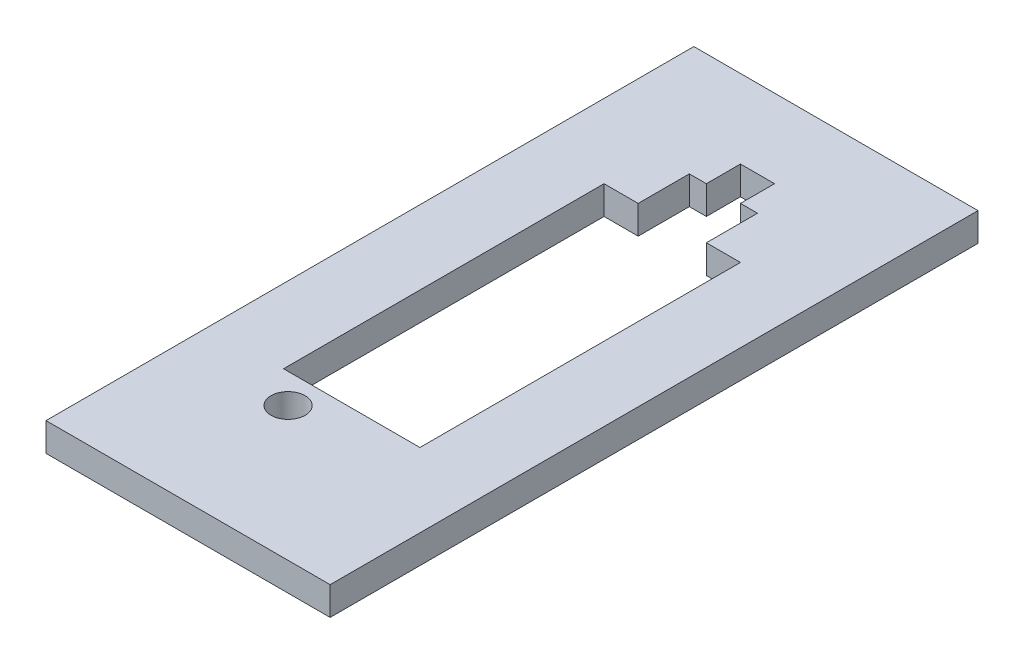
SolidWorks part; units mm, degrees
material "Spruce"
ref_plane "Front Plane" through (0, 0, 0) normal (0, 0, 1) x (1, 0, 0)
ref_plane "Top Plane" through (0, 0, 0) normal (0, 1, 0) x (1, 0, 0)
ref_plane "Right Plane" through (0, 0, 0) normal (1, 0, 0) x (0, 0, -1)
sketch "Sketch1" plane through (0, 0, 0) normal (0, 1, 0) x (1, 0, 0)
  line L1 (-15.875, 36.195) -> (15.875, 36.195)
  line L2 (-15.875, 36.195) -> (-15.875, -36.195)
  line L3 (-15.875, -36.195) -> (15.875, -36.195)
  line L4 (15.875, 36.195) -> (15.875, -36.195)
  line L5 (-15.875, 36.195) -> (15.875, -36.195) construction
  line L6 (-15.875, -36.195) -> (15.875, 36.195) construction
  point P0 (0, 0)
  dimension "D1" = 72.39
  dimension "D2" = 31.75
extrude "Boss-Extrude1" add sketch "Sketch1" along normal blind 3.175
sketch "Sketch3" plane through (0, 3.175, 0) normal (0, 1, 0) x (1, 0, 0)
  line L1 (-7.62, 17.907) -> (7.62, 17.907)
  line L2 (-7.62, 17.907) -> (-7.62, -17.907)
  line L3 (-7.62, -17.907) -> (7.62, -17.907)
  line L4 (7.62, 17.907) -> (7.62, -17.907)
  line L5 (-7.62, 17.907) -> (7.62, -17.907) construction
  line L6 (-7.62, -17.907) -> (7.62, 17.907) construction
  point P0 (0, 0)
  dimension "D1" = 15.24
  dimension "D2" = 35.814
extrude "Cut-Extrude1" cut sketch "Sketch3" against normal up to surface (3.175 mm away) up to face at (0, 0, 0)
sketch "Sketch4" plane through (0, 3.175, 0) normal (0, 1, 0) x (1, 0, 0)
  line L2 (0, 17.907) -> (0, 25.527) construction
  line L3 (0, 36.195) -> (0, 17.907) construction
  line L4 (15.875, 36.195) -> (-15.875, 36.195) construction
  line L6 (7.62, 17.907) -> (-7.62, 17.907) construction
  line L17 (-3.81, 17.907) -> (3.81, 17.907)
  line L18 (-3.81, 23.622) -> (3.81, 23.622)
  line L19 (-3.81, 23.622) -> (-3.81, 17.907)
  line L21 (3.81, 23.622) -> (3.81, 17.907)
  line L22 (-3.81, 23.622) -> (0, 17.907) construction
  line L23 (0, 17.907) -> (3.81, 23.622) construction
  line L25 (-1.905, 27.432) -> (1.905, 27.432)
  line L26 (-1.905, 27.432) -> (-1.905, 23.622)
  line L27 (-1.905, 23.622) -> (1.905, 23.622)
  line L28 (1.905, 27.432) -> (1.905, 23.622)
  line L29 (-1.905, 27.432) -> (1.905, 23.622) construction
  line L30 (-1.905, 23.622) -> (1.905, 27.432) construction
  circle A0 centre (-3.81, -21.209) radius 1.905
  point P5 (0, 17.907)
  point P7 (0, 17.907)
  point P15 (0, 17.907)
  line M7 (-7.62, 17.907) -> (7.62, 17.907)
  dimension "D1" = 7.62
  dimension "D2" = 5.715
  dimension "D3" = 3.81
  dimension "D4" = 3.81
extrude "Cut-Extrude9" cut sketch "Sketch4" against normal up to surface (3.175 mm away) contours L21 L18 L19 M7 | L28 L25 L26 L18 | A0 up to face at (0, 0, 0)
